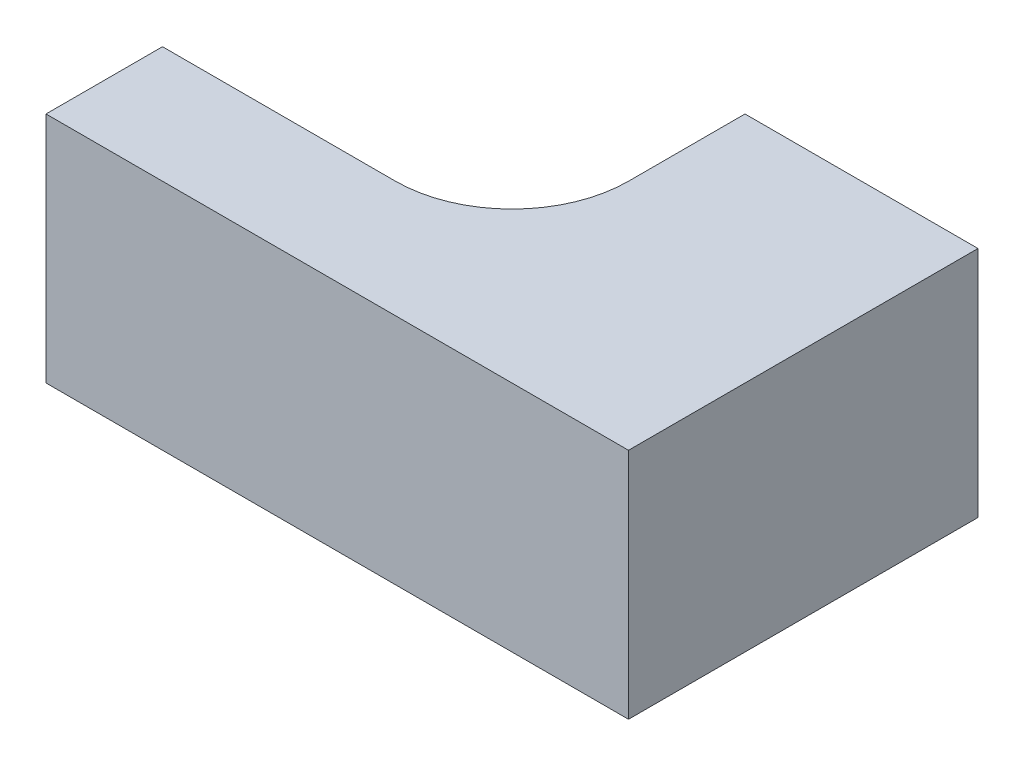
SolidWorks part; units mm, degrees
ref_plane "Přední rovina" through (0, 0, 0) normal (0, 0, 1) x (1, 0, 0)
ref_plane "Horní rovina" through (0, 0, 0) normal (0, 1, 0) x (1, 0, 0)
ref_plane "Pravá rovina" through (0, 0, 0) normal (1, 0, 0) x (0, 0, -1)
sketch "Sketch2" plane through (0, 0, 0) normal (0, 1, 0) x (1, 0, 0)
  line L0 (0, 0) -> (0, -10)
  line L1 (10, -20) -> (30, -20)
  line L2 (30, -20) -> (30, -30)
  line L3 (30, -30) -> (-20, -30)
  line L4 (-20, -30) -> (-20, 0)
  line L5 (-20, 0) -> (0, 0)
  arc A0 (0, -10) -> (10, -20) centre (10, -10) ccw
  dimension "D2" = 10
  dimension "D1" = 20
  dimension "D3" = 20
  dimension "D4" = 10
  dimension "D5" = 10
extrude "Boss-Extrude1" add sketch "Sketch2" along normal blind 20
mirror "Mirror1" about plane through (-20, 20, 30) normal (1, 0, 0) of bodies 101
delete or keep bodies "Body-Delete/Keep 1" type delete bodies bodies 101
equation "\"R\"= 10"
equation "\"D2@Sketch2\"=\"R\""
equation "\"D1@Sketch2\"=\"R\" *2"
equation "\"D3@Sketch2\"=\"R\" * 2"
equation "\"D5@Sketch2\"=\"R\""
equation "\"D4@Sketch2\"=\"R\""
